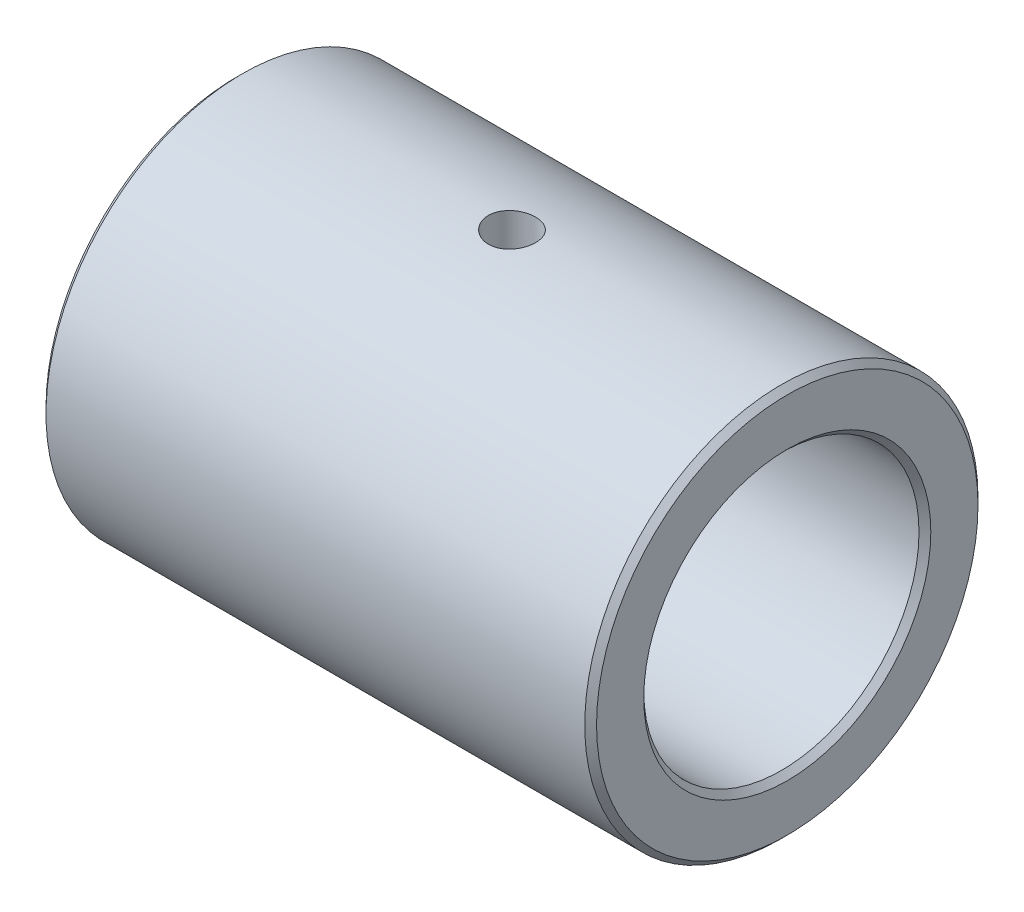
SolidWorks part; units mm, degrees
material "20"
ref_plane "前视基准面" through (0, 0, 0) normal (0, 0, 1) x (1, 0, 0)
ref_plane "上视基准面" through (0, 0, 0) normal (0, 1, 0) x (1, 0, 0)
ref_plane "右视基准面" through (0, 0, 0) normal (1, 0, 0) x (0, 0, -1)
sketch "草图1" plane through (0, 0, 0) normal (1, 0, 0) x (0, 0, -1)
  circle A0 centre (0, 0) radius 50
  circle A1 centre (0, 0) radius 30.5
  dimension "D1" = 100
  dimension "D2" = 61
extrude "凸台-拉伸1" add sketch "草图1" along normal mid plane 140
sketch "草图4" plane through (-70, 0, 0) normal (-1, 0, 0) x (0, 0, 1)
  circle A0 centre (0, 0) radius 35
  dimension "D1" = 70
extrude "切除-拉伸1" cut sketch "草图4" against normal blind 61
sketch "草图5" plane through (70, 0, 0) normal (1, 0, 0) x (0, 0, -1)
  circle A0 centre (0, 0) radius 35
  dimension "D1" = 70
extrude "切除-拉伸2" cut sketch "草图5" against normal blind 61
ref_plane "基准面1" through (0, 50, 0) normal (0, 1, 0) x (1, 0, 0)
chamfer "倒角1" distance 1.5 angle 45 4 edges at (70, 0, -50) (-70, 0, -50) (70, 0, -35) (-70, 0, 35)
hole_wizard "M14 螺纹孔1" positions "草图2" profile "草图3" tap size "M14" standard "GB"
sketch "草图2" plane through (0, 50, 0) normal (0, 1, 0) x (1, 0, 0)
  line L0 (70, -48.5) -> (70, 48.5) construction
  line L1 (68.5, 50) -> (-68.5, 50) construction
  point P0 (0, 0)
  dimension "D1" = 70
  dimension "D2" = 50
sketch "草图3" plane through (0, 50, 0) normal (1, 0, 0) x (0, 0, 1)
  line L0 (0, 0) -> (0, 41.6052)
  line L1 (0, 41.6052) -> (6, 38)
  line L2 (6, 38) -> (6, 0)
  line L5 (6, 0) -> (0, 0)
  line L10 (0, 41.6052) -> (-6, 38) construction
  line L11 (0, -6.35) -> (0, 107.95) construction
  dimension "螺纹孔钻头直径" = 12
  dimension "螺纹孔钻头深度" = 38
  dimension "导头角度" = 118
cosmetic thread "孔螺蚊线1" parameters "D1"=20.6061, "D2"=14
